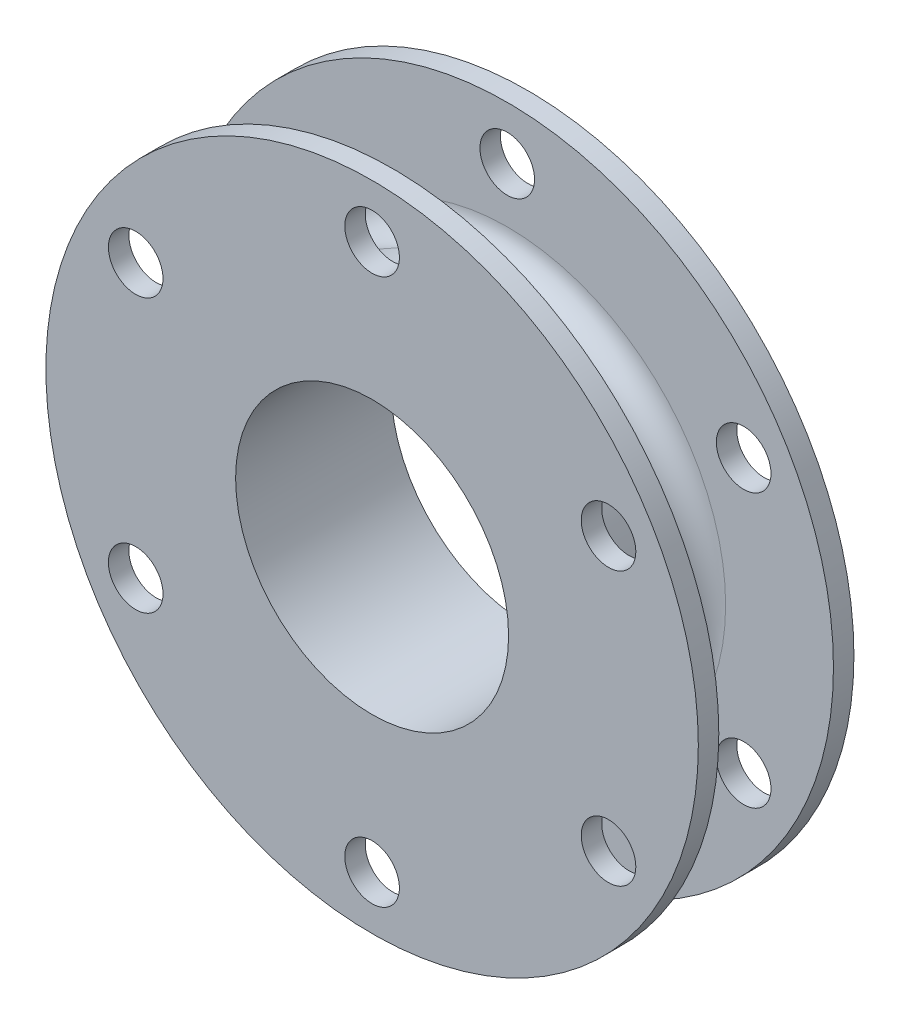
SolidWorks part; units mm, degrees
ref_plane "Plano frontal" through (0, 0, 0) normal (0, 0, 1) x (1, 0, 0)
ref_plane "Plano superior" through (0, 0, 0) normal (0, 1, 0) x (1, 0, 0)
ref_plane "Plano direito" through (0, 0, 0) normal (1, 0, 0) x (0, 0, -1)
sketch "Esboço1" plane through (0, 0, 0) normal (0, 0, 1) x (1, 0, 0)
  circle A0 centre (0, 0) radius 23.9 construction
  circle A1 centre (0, 0) radius 23.9
  circle A2 centre (0, -20) radius 2 construction
  circle A3 centre (-17.3205, -10) radius 2 construction
  circle A4 centre (-17.3205, 10) radius 2 construction
  circle A5 centre (17.3205, -10) radius 2 construction
  circle A6 centre (17.3205, 10) radius 2 construction
  circle A7 centre (0, 20) radius 2 construction
  circle A8 centre (0, -20) radius 2
  circle A9 centre (-17.3205, -10) radius 2
  circle A10 centre (-17.3205, 10) radius 2
  circle A11 centre (17.3205, -10) radius 2
  circle A12 centre (17.3205, 10) radius 2
  circle A13 centre (0, 20) radius 2
  circle A14 centre (0, 0) radius 7.5 construction
  circle A15 centre (0, 0) radius 7.5 construction
  circle A16 centre (0, 0) radius 10
  dimension "D1" = 2.5
extrude "Ressalto-extrusão1" add sketch "Esboço1" along normal blind 1.5
sketch "Esboço2" plane through (0, 0, 1.5) normal (0, 0, 1) x (1, 0, 0)
  circle A0 centre (0, 0) radius 10 construction
  circle A1 centre (0, 0) radius 10
  circle A2 centre (0, 0) radius 14
  dimension "D1" = 4
extrude "Ressalto-extrusão2" add sketch "Esboço2" along normal up to surface (9.9 mm away)
sketch "Esboço3" plane through (0, 0, 11.4) normal (0, 0, 1) x (1, 0, 0)
  circle A0 centre (0, 0) radius 23.9 construction
  circle A1 centre (0, 0) radius 23.9
  circle A2 centre (-17.3205, -10) radius 2 construction
  circle A3 centre (0, -20) radius 2 construction
  circle A4 centre (17.3205, -10) radius 2 construction
  circle A5 centre (17.3205, 10) radius 2 construction
  circle A6 centre (0, 20) radius 2 construction
  circle A7 centre (-17.3205, 10) radius 2 construction
  circle A8 centre (0, 0) radius 10 construction
  circle A9 centre (-17.3205, -10) radius 2
  circle A10 centre (0, -20) radius 2
  circle A11 centre (17.3205, -10) radius 2
  circle A12 centre (17.3205, 10) radius 2
  circle A13 centre (0, 20) radius 2
  circle A14 centre (-17.3205, 10) radius 2
  circle A15 centre (0, 0) radius 10
extrude "Ressalto-extrusão3" add sketch "Esboço3" against normal blind 1.5
fillet "Filete1" radius 2 2 edges at (14, 0, 9.9) (14, 0, 1.5)
